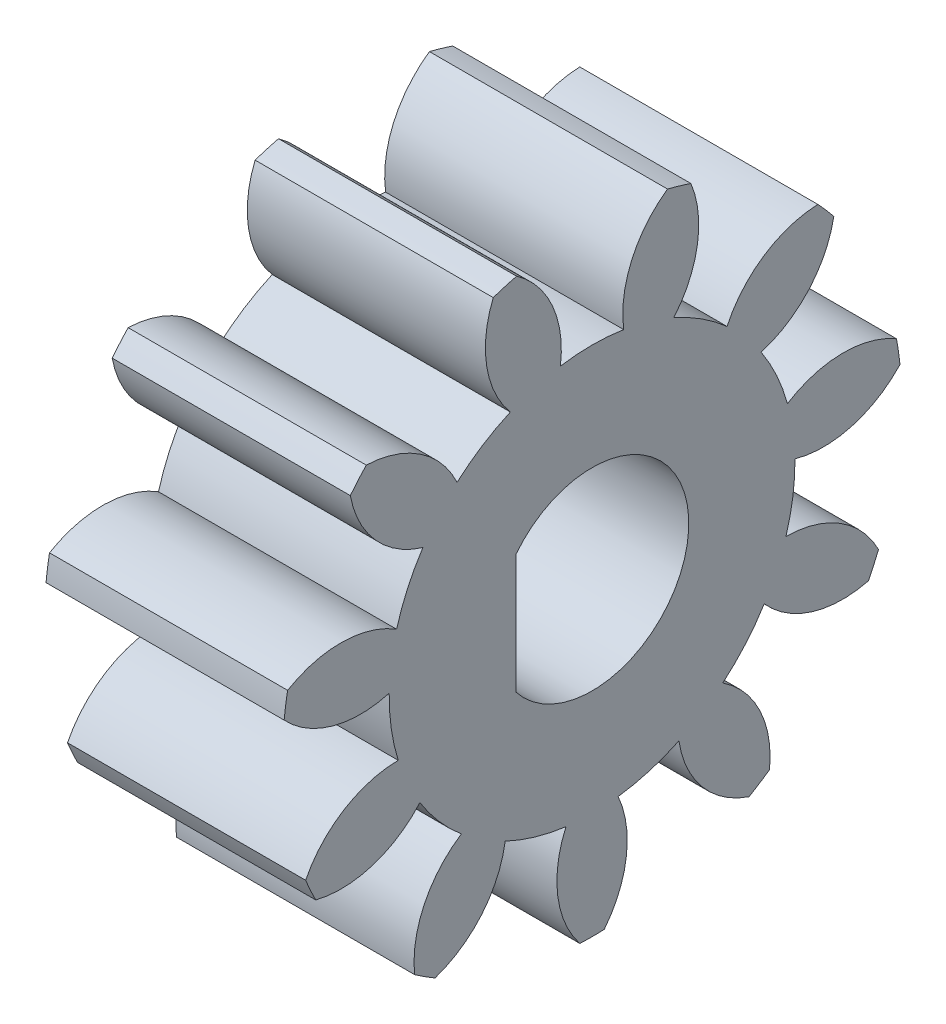
SolidWorks part; units mm, degrees
ref_plane "Plane1" through (0, 0, 0) normal (0, 0, 1) x (1, 0, 0)
ref_plane "Plane2" through (0, 0, 0) normal (0, 1, 0) x (1, 0, 0)
ref_plane "Plane3" through (0, 0, 0) normal (1, 0, 0) x (0, 0, -1)
sketch "HoldingSke" plane through (0, 0, 0) normal (0, 1, 0) x (1, 0, 0)
  line L0 (0, 0) -> (498.6666, -96.931)
  line L1 (-15, 0) -> (100, 0) construction
  line L2 (0, 0) -> (-2.1039, 2.3779)
  line L3 (0, 0) -> (-11.863, 4.5341)
  line L4 (0, 0) -> (8.4773, 1.6478)
  line L5 (0, 0) -> (-47.5972, -17.7524)
  line L6 (0, 0) -> (-5.2639, -3.5516)
  line L7 (-2.1039, 2.3779) -> (8.8308, 51.9871)
  line L8 (-76.2, 54.61) -> (-72.771, 54.61)
  line L9 (-67.7845, 28.3722) -> (-49.3413, 33.142)
  line L10 (-76.2, 71.12) -> (104.1128, 71.12)
  line L11 (0, 0) -> (-6.35, 0)
  line L12 (-76.2, 101.6) -> (-76.1492, 101.6)
  line L13 (24.9733, 27.94) -> (52.9518, 28.4284)
  line L14 (24.9733, 27.94) -> (25.0241, 27.9398)
  line L15 (24.9733, 27.94) -> (100.4021, 29.52)
  circle A0 centre (0, 0) radius 1.5875
  circle A1 centre (0, 0) radius 5.4102
  circle A2 centre (0, 0) radius 38.1
  circle A3 centre (0, 0) radius 1.5875
  dimension "MHD" = 10.8204
  dimension "Hub_dia" = 76.2
  dimension "Bore" = 3.175
  dimension "MBD" = 3.175
  dimension "Num_teeth" = 11
  dimension "Pitch" = 508
  dimension "Overall_len" = 50.8
  dimension "Show_teeth" = 11
  dimension "Thickness" = 6.35
  dimension "OAL" = 50.8001
  dimension "T_dim" = 3.429
  dimension "Ap" = 14.5
  dimension "H" = 19.05
  dimension "Pitch_radius" = 180.3128
  dimension "Width" = 6.35
  dimension "Backlash" = 0.0508
  dimension "Addendum_fac" = 1
  dimension "Dedendum_fac" = 1.2
  dimension "Clearance_fac" = 0.2
  dimension "Dedendum_add" = 0.0508
sketch "BasProSke" plane through (0, 0, 0) normal (0, 1, 0) x (1, 0, 0)
  line L0 (-10, 0) -> (60, 0) construction
  line L1 (0, 0) -> (0, 8.255)
  line L2 (0, 0) -> (6.35, 0)
  line L3 (6.35, 0) -> (6.35, 8.255)
  line L4 (6.35, 8.255) -> (0, 8.255)
  dimension "Thickness" = 6.35
  dimension "Diameter" = 16.51
revolve "Base-Revolve" add sketch "BasProSke" angle 360 about L0
sketch "TooCutSke" plane through (0, 0, 0) normal (1, 0, 0) x (0, 0, -1)
  line L1 (0, 0) -> (0, 107) construction
  line L2 (0, 0) -> (-1.0828, 6.9006) construction
  line L3 (0, 0) -> (-3.9026, 13.2911) construction
  line L4 (-1.0828, 6.9006) -> (-1.9513, 6.6455) construction
  arc A0 (0.8443, 5.3439) -> (-0.8443, 5.3439) centre (0, 0) ccw
  arc A1 (2.0401, 8.0252) -> (-2.0401, 8.0252) centre (0, 0) ccw
  circle A2 centre (0, 0) radius 6.985 construction
  circle A3 centre (0, 0) radius 6.7625 construction
  arc A4 (-0.8443, 5.3439) -> (-2.0401, 8.0252) centre (-3.6134, 5.7162) ccw
  arc A5 (2.0401, 8.0252) -> (0.8443, 5.3439) centre (3.6134, 5.7162) ccw
  dimension "Root_dia" = 10.8204
  dimension "Overcut_dia" = 16.5608
  dimension "Pitch_dia" = 13.97
  dimension "Base_dia" = 13.525
  dimension "Flank_rad" = 2.794
  dimension "Half_ang" = 16.364
  dimension "Half_CT" = 0.9052
extrude "ToothCut" cut sketch "TooCutSke" along normal through all
fillet "Breaks" [suppressed] radius 0.0254
fillet "RootFillets" [suppressed] radius 0.3048
pattern_circular "TeethCuts" count 11 every 32.727 about axis through (-10, 0, 0) along (1, 0, 0) of "ToothCut", "RootFillets", "Breaks"
sketch "HubNeaOneSke" plane through (0, 0, 0) normal (-1, 0, 0) x (0, 0, 1)
  circle A0 centre (0, 0) radius 5.4102
  dimension "Diameter" = 10.8204
extrude "HubNearOne" [suppressed] add sketch "HubNeaOneSke" along normal blind 44.4501
sketch "HubNeaBotSke" plane through (0, 0, 0) normal (-1, 0, 0) x (0, 0, 1)
  circle A0 centre (0, 0) radius 5.4102
  dimension "Diameter" = 10.8204
extrude "HubNearBoth" [suppressed] add sketch "HubNeaBotSke" along normal blind 22.225
ref_plane "FarPln" through (6.35, 0, 0) normal (1, 0, 0) x (0, 0, -1)
sketch "HubFarSke" plane through (6.35, 0, 0) normal (1, 0, 0) x (0, 0, -1)
  circle A0 centre (0, 0) radius 5.4102
  dimension "Diameter" = 10.8204
extrude "HubFar" [suppressed] add sketch "HubFarSke" along normal blind 22.225
sketch "BorSke" plane through (0, 0, 0) normal (1, 0, 0) x (0, 0, -1)
  circle A0 centre (0, 0) radius 1.5875
  dimension "Diameter" = 3.175
extrude "Bore" cut sketch "BorSke" along normal mid plane 101.6001
sketch "KeySke" plane through (0, 0, 0) normal (1, 0, 0) x (0, 0, -1)
  line L0 (-0.127, 0) -> (-0.127, 1.8415)
  line L1 (-0.127, 1.8415) -> (0.127, 1.8415)
  line L2 (0.127, 1.8415) -> (0.127, 0)
  line L3 (0, 0) -> (0, 34) construction
  line L4 (-0.127, 0) -> (0.127, 0)
  dimension "Offset" = 1.8415
  dimension "Width" = 0.254
extrude "Keyway" [suppressed] cut sketch "KeySke" along normal mid plane 101.6001
pattern_circular "Keyway2" [suppressed] count 2 every 90 about axis through (-10, 0, 0) along (1, 0, 0)
sketch "Sketch3" plane through (0, 0, 0) normal (-1, 0, 0) x (0, 0, 1)
  line L0 (0, 0) -> (2.5797, 0) construction
  line L1 (2.5797, -1.5875) -> (2.5797, 1.5875) construction
  line L2 (2.5797, 1.5875) -> (2.0334, 1.5875) construction
  line L3 (2.0334, 1.5875) -> (2.0334, -1.5875)
  circle A0 centre (0, 0) radius 1.5875 construction
  circle A1 centre (0, 0) radius 1.5875
  circle A2 centre (0, 0) radius 2.5797
  point P7 (2.5797, 0)
  circle M7 centre (0, 0) radius 1.5875
  dimension "D1" = 5.1594
  dimension "D2" = 3.175
extrude "Cut-Extrude1" cut sketch "Sketch3" against normal up to next contours L3 A2 M7
equation "' \"Pitch@HoldingSke\" = 4"
equation "' \"Num_teeth@HoldingSke\" = 12"
equation "' \"Ap@HoldingSke\" =  20"
equation "' \"Ap@HoldingSke\" = 20"
equation "' \"Width@HoldingSke\" = 0.5"
equation "' \"Hub_dia@HoldingSke\"= 1"
equation "' \"Hub_dia@HoldingSke\" = 1"
equation "' \"Overall_len@HoldingSke\" = 1.0"
equation "' \"Bore@HoldingSke\" = 0.75"
equation "' \"T_dim@HoldingSke\" = 0.85"
equation "' \"Width@KeySke\" = 0.25"
equation "' \"Show_teeth@HoldingSke\" = 13"
equation "' \"Backlash@HoldingSke\" = 0.009"
equation "' \"Addendum_fac@HoldingSke\" = 1.0"
equation "' \"Dedendum_fac@HoldingSke\" = 1.25"
equation "' \"Dedendum_add@HoldingSke\" = 0.00005"
equation "' \"Clearance_fac@HoldingSke\" = 0.25"
equation "' \"Pitch@HoldingSke\" = 0.5"
equation "' \"Num_teeth@HoldingSke\" = 23"
equation "' \"Show_teeth@HoldingSke\" = 23"
equation "' \"Backlash@HoldingSke\" = 0.0375"
equation "\"Overcut_dia@TooCutSke\" = (\"Num_teeth@HoldingSke\" + 2 * \"Addendum_fac@HoldingSke\") / \"Pitch@HoldingSke\" + 0.002"
equation "\"Pitch_dia@TooCutSke\" = \"Num_teeth@HoldingSke\" / \"Pitch@HoldingSke\""
equation "\"Base_dia@TooCutSke\" = \"Num_teeth@HoldingSke\" / \"Pitch@HoldingSke\" * cos((\"Ap@HoldingSke\"  * 3.14159265 / 180))"
equation "\"Root_dia@TooCutSke\" = (\"Num_teeth@HoldingSke\" + 2) / \"Pitch@HoldingSke\" - 2 * (\"Addendum_fac@HoldingSke\" + \"Dedendum_fac@HoldingSke\") / \"Pitch@HoldingSke\" - \"Dedendum_add@HoldingSke\" * 2"
equation "\"Half_ang@TooCutSke\" = 180 / \"Num_teeth@HoldingSke\""
equation "\"Half_CT@TooCutSke\" = \"Num_teeth@HoldingSke\" / \"Pitch@HoldingSke\" * sin((3.14159265 / 2 / \"Num_teeth@HoldingSke\")) / 2 - 7 * \"Backlash@HoldingSke\" / 4"
equation "\"Flank_rad@TooCutSke\" = \"Num_teeth@HoldingSke\" / \"Pitch@HoldingSke\" / 5"
equation "\"Radius@RootFillets\" = \"Clearance_fac@HoldingSke\" / \"Pitch@HoldingSke\" + \"Dedendum_add@HoldingSke\""
equation "\"Break_rad@Breaks\" = 0.02 / \"Pitch@HoldingSke\""
equation "\"Thickness@HoldingSke\" = \"Width@HoldingSke\""
equation "\"OAL@HoldingSke\" = \"Thickness@HoldingSke\""
equation "\"MHD@HoldingSke\" = (\"Num_teeth@HoldingSke\" + 2) / \"Pitch@HoldingSke\" - 2 * (\"Addendum_fac@HoldingSke\" + \"Dedendum_fac@HoldingSke\")  / \"Pitch@HoldingSke\" - \"Dedendum_add@HoldingSke\" * 2"
equation "\"MBD@HoldingSke\" = (\"Num_teeth@HoldingSke\" + 2) / \"Pitch@HoldingSke\" - 2 * (\"Addendum_fac@HoldingSke\" + \"Dedendum_fac@HoldingSke\")  / \"Pitch@HoldingSke\" - \"Dedendum_add@HoldingSke\" * 2 - 0.002"
equation "\"MHD@HoldingSke\" = ((sgn( \"MHD@HoldingSke\" - \"Hub_dia@HoldingSke\" )-1)*( \"MHD@HoldingSke\" - \"Hub_dia@HoldingSke\" ))/-2+ \"Hub_dia@HoldingSke\""
equation "\"MBD@HoldingSke\" = ((sgn( \"MBD@HoldingSke\" - \"Bore@HoldingSke\" )-1)*( \"MBD@HoldingSke\" - \"Bore@HoldingSke\" ))/-2+ \"Bore@HoldingSke\""
equation "\"OAL@HoldingSke\" = ((sgn( \"OAL@HoldingSke\" - \"Overall_len@HoldingSke\" )+1)*( \"OAL@HoldingSke\" - \"Overall_len@HoldingSke\" ))/2 + \"Overall_len@HoldingSke\" + 0.000002"
equation "\"Num_teeth@TeethCuts\" = int( \"Show_teeth@HoldingSke\" ) + 1"
equation "\"Num_teeth@TeethCuts\" = ((sgn( \"Num_teeth@TeethCuts\" - \"Num_teeth@HoldingSke\" )-1)*( \"Num_teeth@TeethCuts\" - \"Num_teeth@HoldingSke\" ))/-2+ \"Num_teeth@HoldingSke\""
equation "\"Num_teeth@TeethCuts\" = ((sgn( \"Num_teeth@TeethCuts\" - 2.0)+1)*( \"Num_teeth@TeethCuts\" - 2.0))/2 +2.0"
equation "\"Angle@TeethCuts\" = 360.0 / \"Num_teeth@HoldingSke\""
equation "\"Diameter@BasProSke\" = (\"Num_teeth@HoldingSke\" + 2 * \"Addendum_fac@HoldingSke\") / \"Pitch@HoldingSke\""
equation "\"Thickness@BasProSke\"  = \"Thickness@HoldingSke\""
equation "' \"Fillet_rad@BasProSke\" =  \"Thickness@HoldingSke\" * 0.05"
equation "' \"Fillet_rad@BasProSke\" = \"Thickness@HoldingSke\" * 0.05"
equation "\"MHD@HoldingSke\" = ((sgn( \"MHD@HoldingSke\" - \"Root_dia@TooCutSke\" )-1)*( \"MHD@HoldingSke\" - \"Root_dia@TooCutSke\" ))/-2+ \"Root_dia@TooCutSke\""
equation "\"Diameter@HubNeaOneSke\" = \"MHD@HoldingSke\""
equation "\"Length@HubNearOne\" = \"OAL@HoldingSke\" - \"Thickness@BasProSke\""
equation "\"Diameter@HubNeaBotSke\" = \"MHD@HoldingSke\""
equation "\"Length@HubNearBoth\" = ( \"OAL@HoldingSke\" - \"Thickness@BasProSke\" ) / 2.0"
equation "\"Thickness@FarPln\" = \"Thickness@BasProSke\""
equation "\"Diameter@HubFarSke\" = \"MHD@HoldingSke\""
equation "\"Length@HubFar\" = ( \"OAL@HoldingSke\" - \"Thickness@BasProSke\" ) / 2.0"
equation "\"Diameter@BorSke\" = \"MBD@HoldingSke\""
equation "\"D1@Bore\" = \"OAL@HoldingSke\" * 2.0"
equation "\"D1@Keyway\" = \"OAL@HoldingSke\" * 2.0"
equation "\"Offset@KeySke\" = \"T_dim@HoldingSke\" - \"MBD@HoldingSke\" / 2.0"
